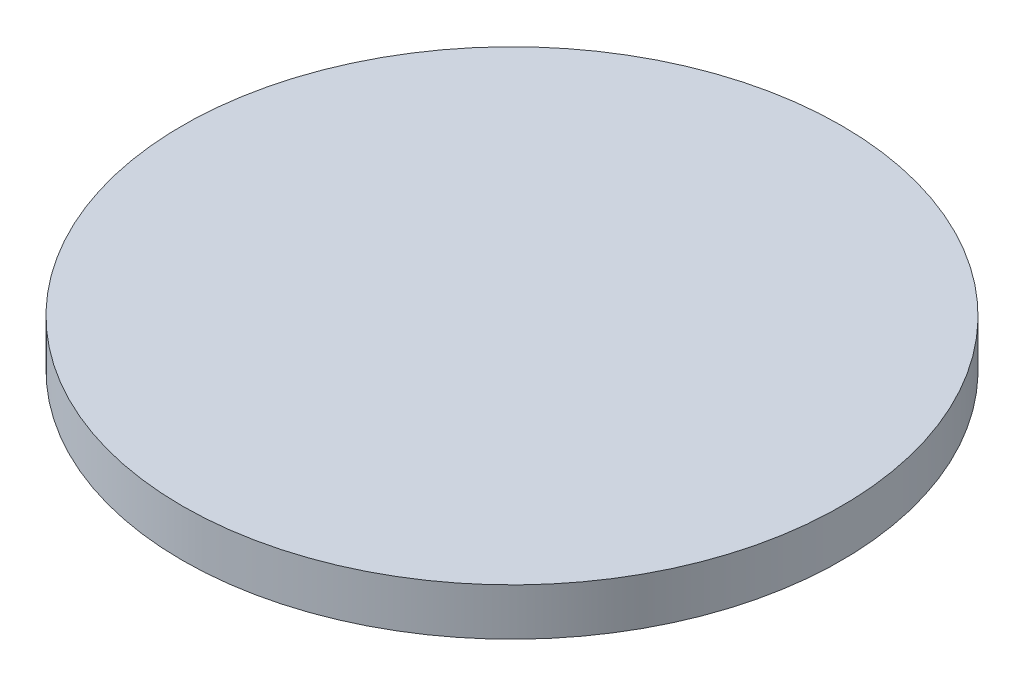
SolidWorks part; units mm, degrees
ref_plane "Front Plane" through (0, 0, 0) normal (0, 0, 1) x (1, 0, 0)
ref_plane "Top Plane" through (0, 0, 0) normal (0, 1, 0) x (1, 0, 0)
ref_plane "Right Plane" through (0, 0, 0) normal (1, 0, 0) x (0, 0, -1)
sketch "Sketch1" plane through (0, 0, 0) normal (0, 1, 0) x (1, 0, 0)
  circle A0 centre (0, 0) radius 70
  dimension "D1" = 140
extrude "Boss-Extrude1" add sketch "Sketch1" along normal blind 10
